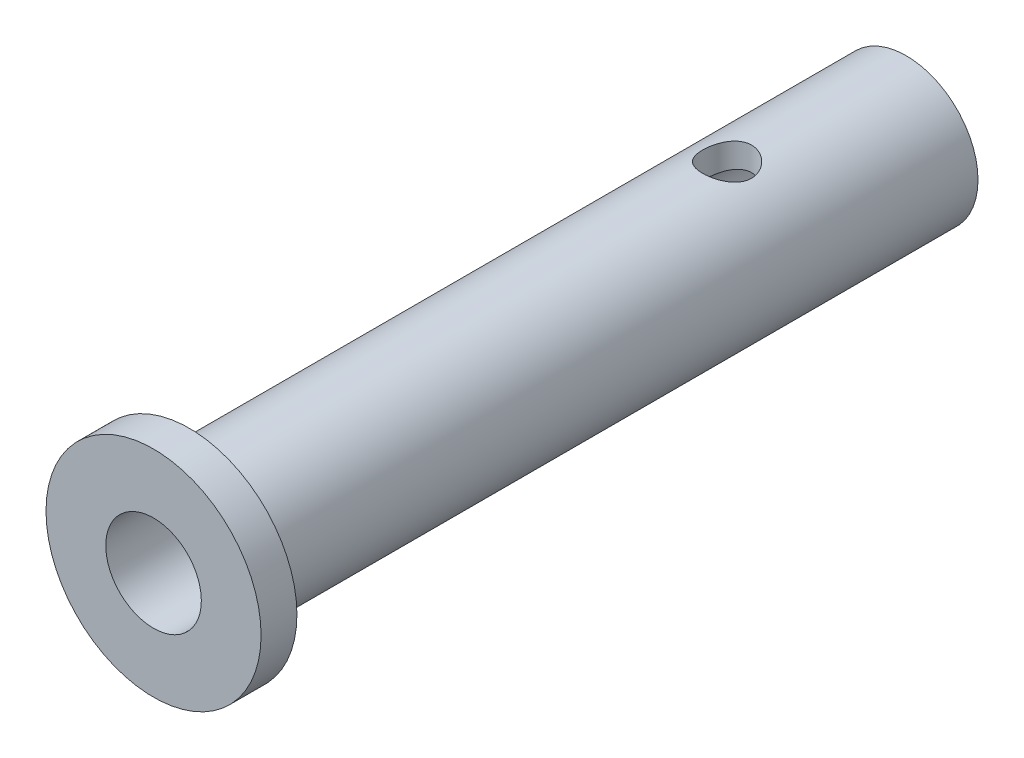
SolidWorks part; units mm, degrees
material "7050-T73510"
ref_plane "前视基准面" through (0, 0, 0) normal (0, 0, 1) x (1, 0, 0)
ref_plane "上视基准面" through (0, 0, 0) normal (0, 1, 0) x (1, 0, 0)
ref_plane "右视基准面" through (0, 0, 0) normal (1, 0, 0) x (0, 0, -1)
sketch "草图1" plane through (0, 0, 0) normal (0, 0, 1) x (1, 0, 0)
  circle A0 centre (0, 0) radius 6
  circle A1 centre (0, 0) radius 4
  dimension "D1" = 12
  dimension "D2" = 8
extrude "凸台-拉伸1" add sketch "草图1" along normal blind 60
sketch "草图2" plane through (0, 0, 60) normal (0, 0, 1) x (1, 0, 0)
  circle A0 centre (0, 0) radius 9
  circle A1 centre (0, 0) radius 4 construction
  circle A2 centre (0, 0) radius 4
  dimension "D1" = 18
extrude "凸台-拉伸2" add sketch "草图2" along normal blind 3
sketch "草图3" plane through (0, 0, 0) normal (0, 1, 0) x (1, 0, 0)
  line L0 (6, 0) -> (-6, 0) construction
  circle A0 centre (0, -15) radius 2.05
  dimension "D1" = 15
  dimension "D2" = 4.1
extrude "切除-拉伸1" cut sketch "草图3" against normal mid plane 50
